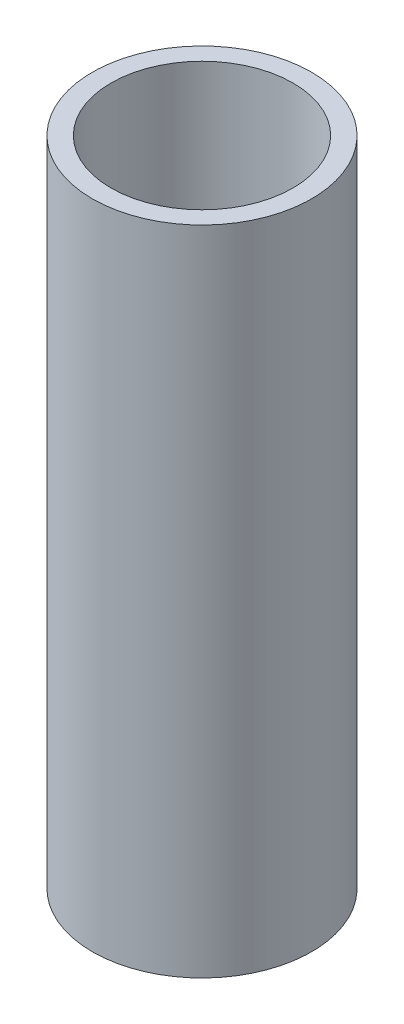
SolidWorks part; units mm, degrees
ref_plane "Front Plane" through (0, 0, 0) normal (0, 0, 1) x (1, 0, 0)
ref_plane "Top Plane" through (0, 0, 0) normal (0, 1, 0) x (1, 0, 0)
ref_plane "Right Plane" through (0, 0, 0) normal (1, 0, 0) x (0, 0, -1)
sketch "Sketch2" plane through (0, 0, 0) normal (0, 1, 0) x (1, 0, 0)
  circle A0 centre (0, 0) radius 4.7752
extrude "Boss-Extrude1" add sketch "Sketch2" along normal blind 28.3972
sketch "Sketch3" plane through (0, 28.3972, 0) normal (0, 1, 0) x (1, 0, 0)
  circle A0 centre (0, 0) radius 3.9624
extrude "Cut-Extrude1" cut sketch "Sketch3" against normal blind 28.3972
